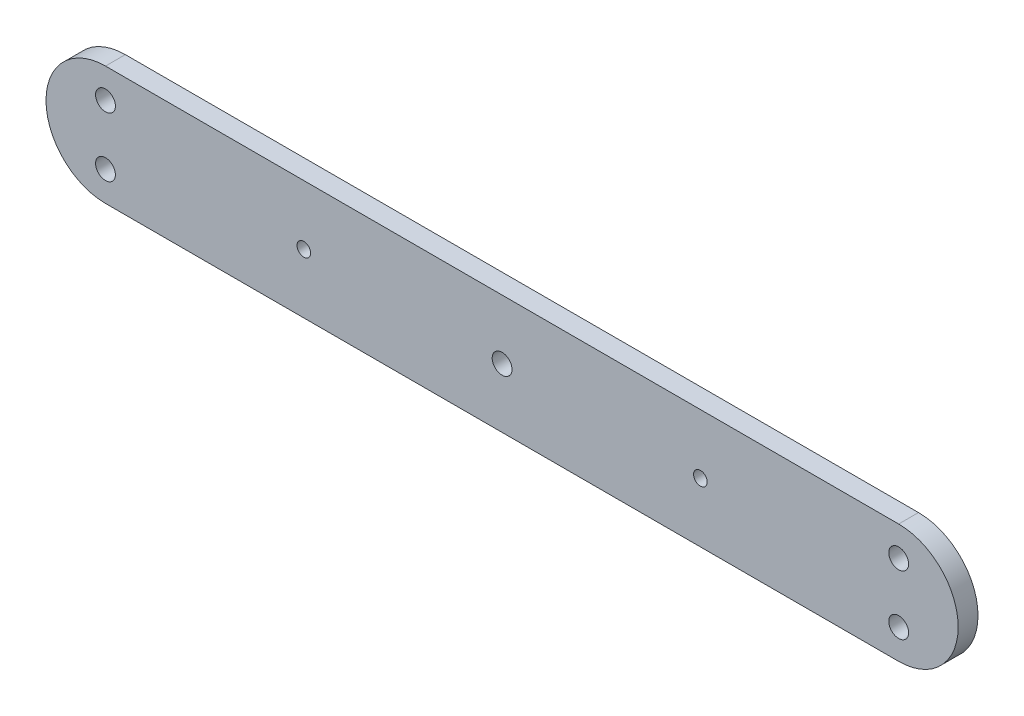
SolidWorks part; units mm, degrees
ref_plane "Front Plane" through (0, 0, 0) normal (0, 0, 1) x (1, 0, 0)
ref_plane "Top Plane" through (0, 0, 0) normal (0, 1, 0) x (1, 0, 0)
ref_plane "Right Plane" through (0, 0, 0) normal (1, 0, 0) x (0, 0, -1)
sketch "Sketch1" plane through (0, 0, 0) normal (0, 0, 1) x (1, 0, 0)
  line L0 (-89.2432, 0) -> (164.7568, 0) construction
  line L1 (-89.2432, 19.05) -> (164.7568, 19.05)
  line L2 (-89.2432, -19.05) -> (164.7568, -19.05)
  line L3 (-89.2432, 0) -> (-89.2432, -9.525) construction
  line L4 (-89.2432, -9.525) -> (164.7568, -9.525) construction
  line L5 (164.7568, -9.525) -> (164.7568, 9.525) construction
  line L6 (164.7568, 9.525) -> (-89.2432, 9.525) construction
  line L7 (-89.2432, 9.525) -> (-89.2432, 0) construction
  arc A0 (-89.2432, 19.05) -> (-89.2432, -19.05) centre (-89.2432, 0) ccw
  arc A1 (164.7568, -19.05) -> (164.7568, 19.05) centre (164.7568, 0) ccw
  circle A3 centre (37.7568, 0) radius 3.175
  circle A5 centre (-25.7432, 0) radius 2.1828
  circle A6 centre (101.2568, 0) radius 2.1828
  circle A7 centre (164.7568, -9.525) radius 3.175
  circle A8 centre (164.7568, 9.525) radius 3.175
  circle A9 centre (-89.2432, 9.525) radius 3.175
  circle A10 centre (-89.2432, -9.525) radius 3.175
  point P3 (37.7568, 0)
  dimension "D3" = 6.35
  dimension "D4" = 6.35
  dimension "D5" = 6.35
  dimension "D6" = 127
  dimension "D7" = 6.35
  dimension "D8" = 4.3656
  dimension "D9" = 4.3656
  dimension "D10" = 9.525
  dimension "D12" = 6.35
  dimension "D1" = 254
  dimension "D2" = 38.1
  dimension "D11" = 9.525
  dimension "D13" = 63.5
extrude "Boss-Extrude1" add sketch "Sketch1" along normal blind 6.35
